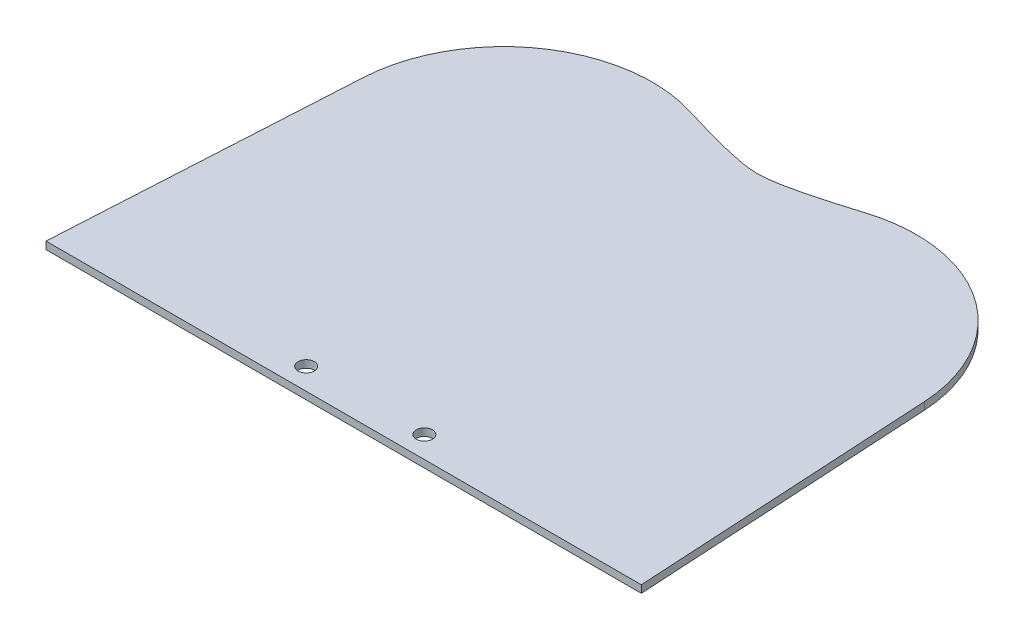
SolidWorks part; units mm, degrees
material "Acrylic (Medium-high impact)"
ref_plane "Front Plane" through (0, 0, 0) normal (0, 0, 1) x (1, 0, 0)
ref_plane "Top Plane" through (0, 0, 0) normal (0, 1, 0) x (1, 0, 0)
ref_plane "Right Plane" through (0, 0, 0) normal (1, 0, 0) x (0, 0, -1)
sketch "Sketch1" plane through (0, 0, 0) normal (0, 1, 0) x (1, 0, 0)
  line L1 (0, 0) -> (160, 0)
  line L2 (0, 0) -> (0, 120)
  line L3 (0, 120) -> (160, 120)
  line L4 (160, 0) -> (160, 120)
  dimension "D1" = 160
  dimension "D2" = 120
extrude "Boss-Extrude1" add sketch "Sketch1" along normal blind 2
sketch "Sketch4" plane through (0, 2, 0) normal (0, 1, 0) x (1, 0, 0)
  line L0 (0, 0) -> (160, 0) construction
  circle A0 centre (95.87, 5.81) radius 2.185
  circle A1 centre (64.12, 5.81) radius 2.185
  dimension "D1" = 4.37
  dimension "D2" = 4.37
  dimension "D3" = 31.75
  dimension "D4" = 5.81
  dimension "D5" = 64.12
  dimension "D6" = 5.81
extrude "Cut-Extrude2" cut sketch "Sketch4" against normal up to surface (2 mm away) up to face at (80, 0, -60)
sketch "Sketch7" plane through (0, 2, 0) normal (0, 1, 0) x (1, 0, 0)
  line L0 (160, 0) -> (155.4151, 80.7542)
  line L1 (80, -6.6662) -> (80, 126.6662) construction
  line L2 (0, 120) -> (0, 0) construction
  line L3 (56.3933, 116.6841) -> (73.7903, 111.2767) construction
  line L4 (103.6067, 116.6841) -> (86.2097, 111.2767) construction
  line L5 (86.2097, 111.2767) -> (80, 111.2767) construction
  line L6 (73.7903, 111.2767) -> (80, 111.2767) construction
  line L7 (0, 0) -> (4.5849, 80.7542)
  line L8 (160, 0) -> (160, 134.8088)
  line L9 (160, 134.8088) -> (0, 134.8088)
  line L10 (0, 134.8088) -> (0, 0)
  arc A0 (155.4151, 80.7542) -> (103.6067, 116.6841) centre (115.4794, 78.4868) ccw
  arc A1 (4.5849, 80.7542) -> (56.3933, 116.6841) centre (44.5206, 78.4868) cw
  spline S0 degree 2 poles (103.6067, 116.6841) (86.2097, 111.2767) (80, 111.2767) knots 0 0 0 1 1 1
  spline S1 degree 2 poles (56.3933, 116.6841) (73.7903, 111.2767) (80, 111.2767) knots 0 0 0 1 1 1
  dimension "D2" = 40
  dimension "D1" = 80
extrude "Cut-Extrude4" cut sketch "Sketch7" against normal up to surface (2 mm away) up to face at (64.12, 0, -7.995)
